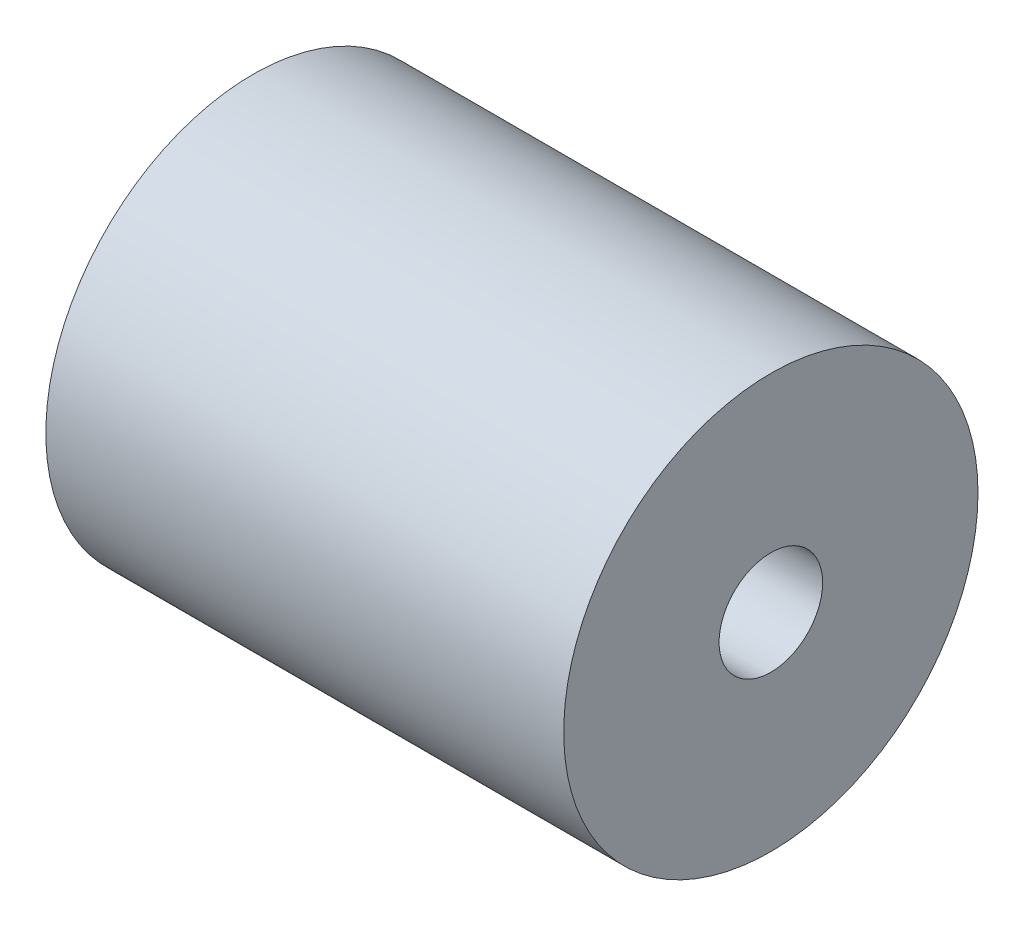
SolidWorks part; units mm, degrees
ref_plane "Front Plane" through (0, 0, 0) normal (0, 0, 1) x (1, 0, 0)
ref_plane "Top Plane" through (0, 0, 0) normal (0, 1, 0) x (1, 0, 0)
ref_plane "Right Plane" through (0, 0, 0) normal (1, 0, 0) x (0, 0, -1)
sketch "Sketch1" plane through (0, 0, 0) normal (1, 0, 0) x (0, 0, -1)
  circle A0 centre (0, 0) radius 10
  dimension "D1" = 20
extrude "Boss-Extrude1" add sketch "Sketch1" along normal mid plane 25
sketch "Sketch2" plane through (0, 0, 0) normal (1, 0, 0) x (0, 0, -1)
  circle A0 centre (0, 0) radius 4
  dimension "D1" = 8
extrude "Cut-Extrude1" cut sketch "Sketch2" against normal through all
sketch "Sketch3" plane through (0, 0, 0) normal (1, 0, 0) x (0, 0, -1)
  circle A0 centre (0, 0) radius 2.5
  dimension "D1" = 5
extrude "Cut-Extrude2" cut sketch "Sketch3" along normal through all
